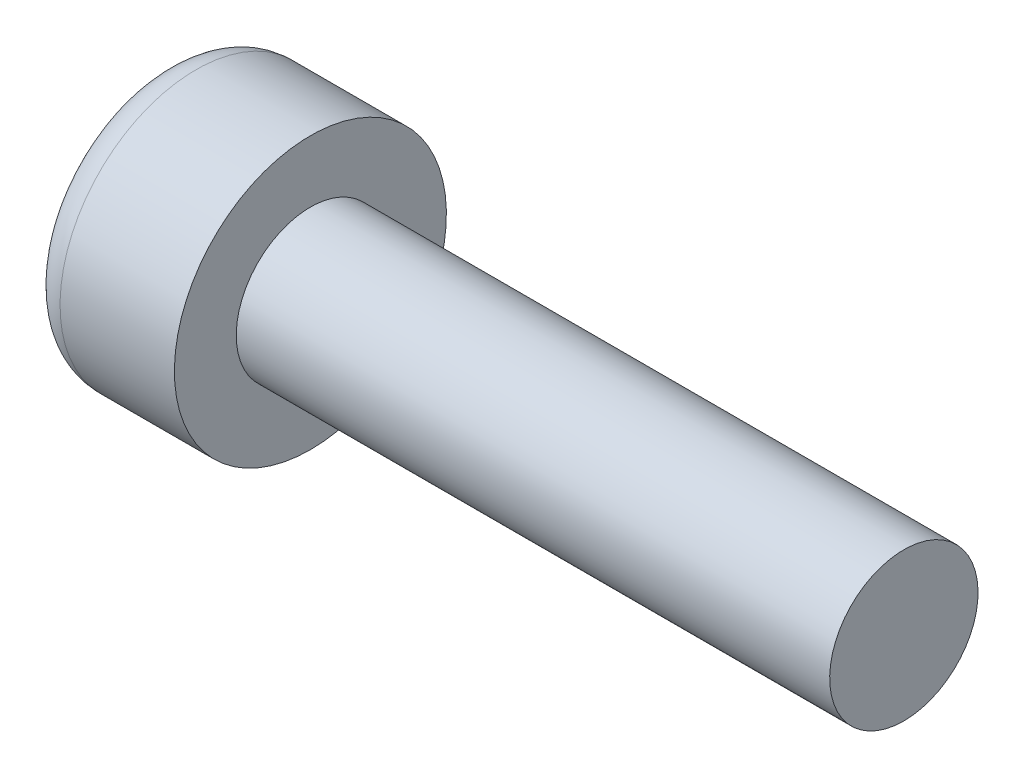
SolidWorks part; units mm, degrees
material "Plain Carbon Steel"
ref_plane "Front Plane" through (0, 0, 0) normal (0, 0, 1) x (1, 0, 0)
ref_plane "Top Plane" through (0, 0, 0) normal (0, 1, 0) x (1, 0, 0)
ref_plane "Right Plane" through (0, 0, 0) normal (1, 0, 0) x (0, 0, -1)
sketch "Sketch1" plane through (0, 0, 0) normal (0, 0, 1) x (1, 0, 0)
  line L0 (0, 0) -> (0, 2.0625)
  line L1 (0.6875, 2.75) -> (3, 2.75)
  line L2 (3, 2.75) -> (3, 1.5)
  line L3 (3, 1.5) -> (15, 1.5)
  line L4 (15, 1.5) -> (15, 0)
  line L5 (15, 0) -> (0, 0) construction
  line L6 (0.6875, 2.0625) -> (0.6875, 1.375) construction
  line L7 (0.6875, 1.375) -> (0.6875, 0.6875) construction
  line L8 (0.6875, 0.6875) -> (0.6875, 0) construction
  line L9 (0.6875, 2.75) -> (0.6875, 2.0625) construction
  line L10 (0, 0) -> (15, 0)
  arc A0 (0, 2.0625) -> (0.6875, 2.75) centre (0.6875, 2.0625) cw
  dimension "D1" = 3
  dimension "D2" = 5.5
  dimension "D3" = 3
  dimension "D4" = 12
revolve "Revolve1" add sketch "Sketch1" angle 360 about L10
sketch "Sketch2" plane through (0, 0, 0) normal (-1, 0, 0) x (0, 0, 1)
  line L1 (0, 1.4434) -> (-1.25, 0.7217)
  line L2 (-1.25, 0.7217) -> (-1.25, -0.7217)
  line L3 (-1.25, -0.7217) -> (0, -1.4434)
  line L4 (0, -1.4434) -> (1.25, -0.7217)
  line L5 (1.25, -0.7217) -> (1.25, 0.7217)
  line L6 (1.25, 0.7217) -> (0, 1.4434)
  circle A0 centre (0, 0) radius 1.25 construction
  dimension "D1" = 2.5
extrude "Cut-Extrude1" cut sketch "Sketch2" against normal blind 1.5
